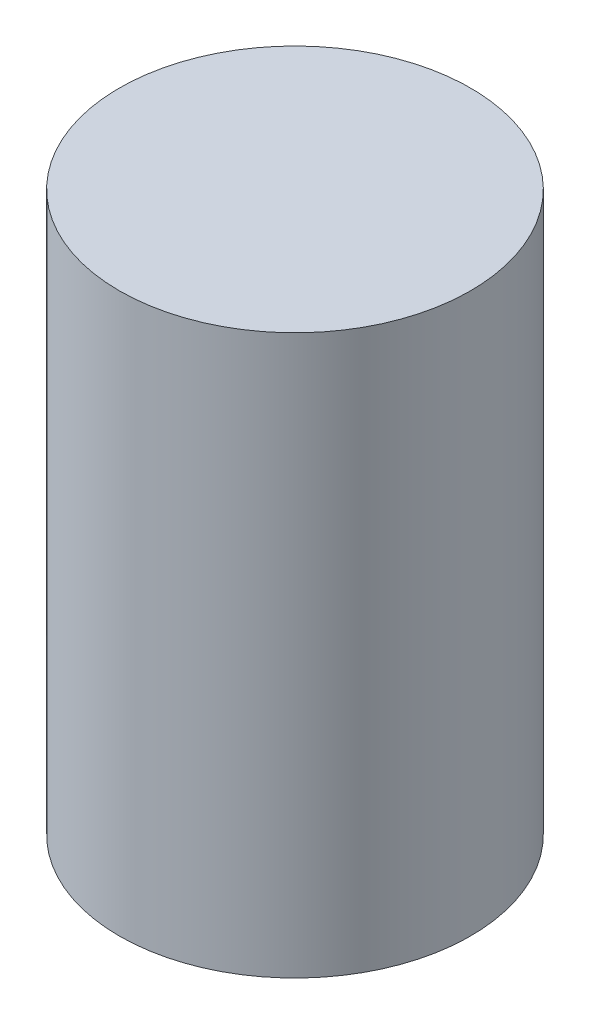
SolidWorks part; units mm, degrees
ref_plane "Front Plane" through (0, 0, 0) normal (0, 0, 1) x (1, 0, 0)
ref_plane "Top Plane" through (0, 0, 0) normal (0, 1, 0) x (1, 0, 0)
ref_plane "Right Plane" through (0, 0, 0) normal (1, 0, 0) x (0, 0, -1)
other "Configuration Table"
sketch "Sketch1" plane through (0, 0, 0) normal (0, 1, 0) x (1, 0, 0)
  circle A0 centre (0, 0) radius 33
extrude "KOLA330_govde_D66" add sketch "Sketch1" along normal blind 105 from offset 3 separate body
